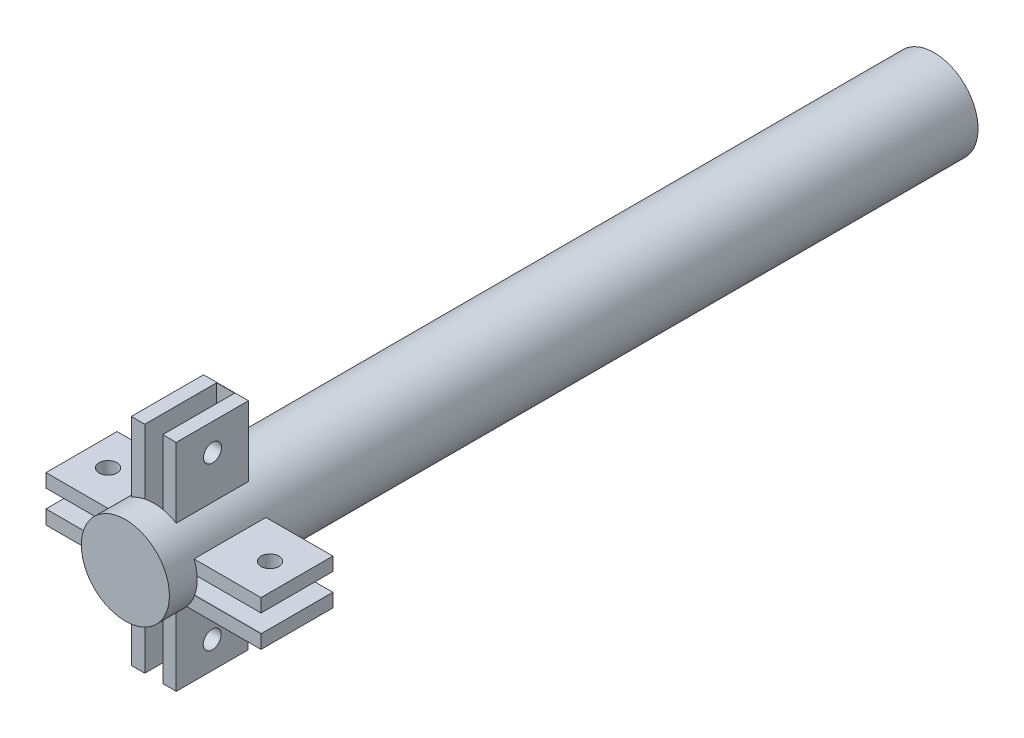
SolidWorks part; units mm, degrees
ref_plane "前视基准面" through (0, 0, 0) normal (0, 0, 1) x (1, 0, 0)
ref_plane "上视基准面" through (0, 0, 0) normal (0, 1, 0) x (1, 0, 0)
ref_plane "右视基准面" through (0, 0, 0) normal (1, 0, 0) x (0, 0, -1)
sketch "草图1" plane through (0, 0, 0) normal (0, 0, 1) x (1, 0, 0)
  circle A0 centre (0, 0) radius 49
  dimension "D1" = 98
extrude "凸台-拉伸1" add sketch "草图1" along normal blind 800
ref_plane "基准面4" through (0, 0, 0) normal (0, -0.7071, 0.7071) x (1, 0, 0)
ref_plane "基准面5" through (-49, 0, 0) normal (-1, 0, 0) x (0, 0, 1)
sketch "草图3" plane through (-49, 0, 0) normal (-1, 0, 0) x (0, 0, 1)
  line L1 (689.0626, 18.2657) -> (769.0626, 18.2657)
  line L2 (689.0626, 18.2657) -> (689.0626, -31.7343)
  line L3 (689.0626, -31.7343) -> (769.0626, -31.7343)
  line L4 (769.0626, 18.2657) -> (769.0626, -31.7343)
  line L5 (689.0626, 18.2657) -> (769.0626, -31.7343) construction
  line L6 (689.0626, -31.7343) -> (769.0626, 18.2657) construction
  point P0 (729.0626, -6.7343)
  dimension "D1" = 80
  dimension "D2" = 50
sketch "草图5" plane through (0, 0, 800) normal (0, 0, 1) x (1, 0, 0)
  line L0 (4.1327, 48.8254) -> (-4.1327, -48.8254) construction
  line L1 (-48.0824, 9.4384) -> (48.0824, -9.4384) construction
  line L2 (48.0824, -9.4384) -> (47.8151, -9.3859) construction
  circle A0 centre (0, 0) radius 49 construction
sketch "草图6" plane through (0, 0, 0) normal (1, 0, 0) x (0, 0, -1)
  line L1 (-769.0626, 18.2657) -> (-689.0626, 18.2657)
  line L2 (-769.0626, 18.2657) -> (-769.0626, -31.7343)
  line L3 (-769.0626, -31.7343) -> (-689.0626, -31.7343)
  line L4 (-689.0626, 18.2657) -> (-689.0626, -31.7343)
  line L5 (-769.0626, 18.2657) -> (-689.0626, -31.7343) construction
  line L6 (-769.0626, -31.7343) -> (-689.0626, 18.2657) construction
  point P0 (-729.0626, -6.7343)
extrude "凸台-拉伸4" add sketch "草图6" along normal blind 120
sketch "草图7" plane through (0, 0, 0) normal (1, 0, 0) x (0, 0, -1)
  line L1 (-768.3488, 18.3839) -> (-689.2798, 18.3839)
  line L2 (-768.3488, 18.3839) -> (-768.3488, -32.1882)
  line L3 (-768.3488, -32.1882) -> (-689.2798, -32.1882)
  line L4 (-689.2798, 18.3839) -> (-689.2798, -32.1882)
  line L5 (-768.3488, 18.3839) -> (-689.2798, -32.1882) construction
  line L6 (-768.3488, -32.1882) -> (-689.2798, 18.3839) construction
  point P0 (-728.8143, -6.9022)
extrude "凸台-拉伸5" add sketch "草图7" against normal blind 120
sketch "草图8" plane through (0, 0, 0) normal (0, 1, 0) x (1, 0, 0)
  line L1 (-25, -688.0375) -> (25, -688.0375)
  line L2 (-25, -688.0375) -> (-25, -768.0375)
  line L3 (-25, -768.0375) -> (25, -768.0375)
  line L4 (25, -688.0375) -> (25, -768.0375)
  line L5 (-25, -688.0375) -> (25, -768.0375) construction
  line L6 (-25, -768.0375) -> (25, -688.0375) construction
  point P0 (0, -728.0375)
  dimension "D1" = 50
  dimension "D2" = 80
extrude "凸台-拉伸6" add sketch "草图8" along normal blind 120
sketch "草图11" plane through (0, 120, 0) normal (0, 1, 0) x (1, 0, 0)
  line L0 (25, -768.0375) -> (25, -688.0375) construction
  line L1 (-25, -688.4084) -> (25, -688.4084)
  line L2 (-25, -688.4084) -> (-25, -768.4084)
  line L3 (-25, -768.4084) -> (25, -768.4084)
  line L4 (25, -688.4084) -> (25, -768.4084)
  line L5 (-25, -688.4084) -> (25, -768.4084) construction
  line L6 (-25, -768.4084) -> (25, -688.4084) construction
  point P0 (0, -728.4084)
  dimension "D1" = 50
  dimension "D2" = 80
extrude "凸台-拉伸7" add sketch "草图11" against normal blind 240
sketch "草图12" plane through (-120, 0, 0) normal (-1, 0, 0) x (0, 0, 1)
  line L0 (768.3488, 18.3839) -> (768.3488, -32.1882) construction
  line L1 (687.3488, 3.3839) -> (768.3488, 3.3839)
  line L2 (687.3488, 3.3839) -> (687.3488, -16.6161)
  line L3 (687.3488, -16.6161) -> (768.3488, -16.6161)
  line L4 (768.3488, 3.3839) -> (768.3488, -16.6161)
  line L5 (687.3488, 3.3839) -> (768.3488, -16.6161) construction
  line L6 (687.3488, -16.6161) -> (768.3488, 3.3839) construction
  point P0 (727.8488, -6.6161)
  dimension "D1" = 81
  dimension "D2" = 20
  dimension "D3" = 15
extrude "切除-拉伸2" cut sketch "草图12" against normal blind 240
sketch "草图13" plane through (120, 0, 0) normal (1, 0, 0) x (0, 0, -1)
  line L0 (-768.3488, -16.6161) -> (-768.3488, 3.3839) construction
  line L1 (-769.1256, 3.4098) -> (-768.3488, 3.4098)
  line L2 (-769.1256, 3.4098) -> (-769.1256, -16.5644)
  line L3 (-769.1256, -16.5644) -> (-768.3488, -16.5644)
  line L4 (-768.3488, 3.4098) -> (-768.3488, -16.5644)
  line L5 (-769.1256, 3.4098) -> (-768.3488, -16.5644) construction
  line L6 (-769.1256, -16.5644) -> (-768.3488, 3.4098) construction
  point P0 (-768.7372, -6.5773)
extrude "切除-拉伸3" cut sketch "草图13" against normal blind 240
sketch "草图14" plane through (0, -120, 0) normal (0, -1, 0) x (-1, 0, 0)
  line L0 (25, -688.4084) -> (-25, -688.4084) construction
  line L1 (10, -768.4084) -> (-10, -768.4084)
  line L2 (10, -768.4084) -> (10, -688.4084)
  line L3 (10, -688.4084) -> (-10, -688.4084)
  line L4 (-10, -768.4084) -> (-10, -688.4084)
  line L5 (10, -768.4084) -> (-10, -688.4084) construction
  line L6 (10, -688.4084) -> (-10, -768.4084) construction
  point P0 (0, -728.4084)
  dimension "D1" = 80
  dimension "D2" = 20
  dimension "D3" = 15
extrude "切除-拉伸4" cut sketch "草图14" against normal blind 240
sketch "草图15" plane through (0, 18.3839, 0) normal (0, 1, 0) x (1, 0, 0)
  line L0 (-120, -689.2798) -> (-45.4206, -689.2798) construction
  line L1 (-120, -689.2798) -> (-120, -768.3488) construction
  circle A0 centre (-90, -729.2798) radius 10
  dimension "D3" = 20
  dimension "D1" = 40
  dimension "D2" = 30
extrude "切除-拉伸5" cut sketch "草图15" against normal blind 240
sketch "草图16" plane through (-25, 0, 0) normal (-1, 0, 0) x (0, 0, 1)
  line L0 (688.0375, 120) -> (768.4084, 120) construction
  line L1 (688.0375, 120) -> (688.0375, 42.1426) construction
  circle A0 centre (728.0375, 90) radius 10
  dimension "D1" = 20
  dimension "D2" = 30
  dimension "D3" = 40
extrude "切除-拉伸7" cut sketch "草图16" against normal blind 240
sketch "草图17" plane through (0, 18.2657, 0) normal (0, 1, 0) x (1, 0, 0)
  line L0 (120, -689.0626) -> (45.4683, -689.0626) construction
  line L1 (120, -689.0626) -> (120, -769.0626) construction
  circle A0 centre (90, -729.0626) radius 10
  dimension "D1" = 20
  dimension "D2" = 40
  dimension "D3" = 30
extrude "切除-拉伸8" cut sketch "草图17" against normal blind 240
sketch "草图18" plane through (25, 0, 0) normal (1, 0, 0) x (0, 0, -1)
  line L0 (-688.4084, -120) -> (-688.4084, -42.1426) construction
  line L1 (-768.4084, -120) -> (-688.4084, -120) construction
  circle A0 centre (-728.4084, -90) radius 10
  point P6 (-728.4084, -120)
  dimension "D1" = 20
  dimension "D2" = 40
  dimension "D3" = 30
extrude "切除-拉伸9" cut sketch "草图18" against normal blind 240
sketch "草图19" plane through (0, 0, 800) normal (0, 0, 1) x (1, 0, 0)
  circle A0 centre (0, 0) radius 37.3103
sketch "草图20" plane through (0, 0, 800) normal (0, 0, 1) x (1, 0, 0)
  circle A0 centre (0, 0) radius 49
extrude "凸台-拉伸11" add sketch "草图20" along normal blind 600
extrude "切除-拉伸10" cut sketch "草图19" along normal through all contours A0
sketch "草图21" plane through (0, 0, 1400) normal (0, 0, 1) x (1, 0, 0)
  circle A0 centre (0, 0) radius 49
extrude "切除-拉伸11" cut sketch "草图21" against normal blind 600
sketch "草图22" plane through (0, 0, 0) normal (0, 0, -1) x (-1, 0, 0)
  circle A0 centre (0, 0) radius 49
extrude "凸台-拉伸12" add sketch "草图22" along normal blind 600
sketch "草图23" plane through (0, 0, -600) normal (0, 0, -1) x (-1, 0, 0)
  line L0 (-4.1327, 48.8254) -> (4.1327, -48.8254) construction
  circle A0 centre (0, 0) radius 49
extrude "切除-拉伸13" cut sketch "草图23" against normal blind 500
